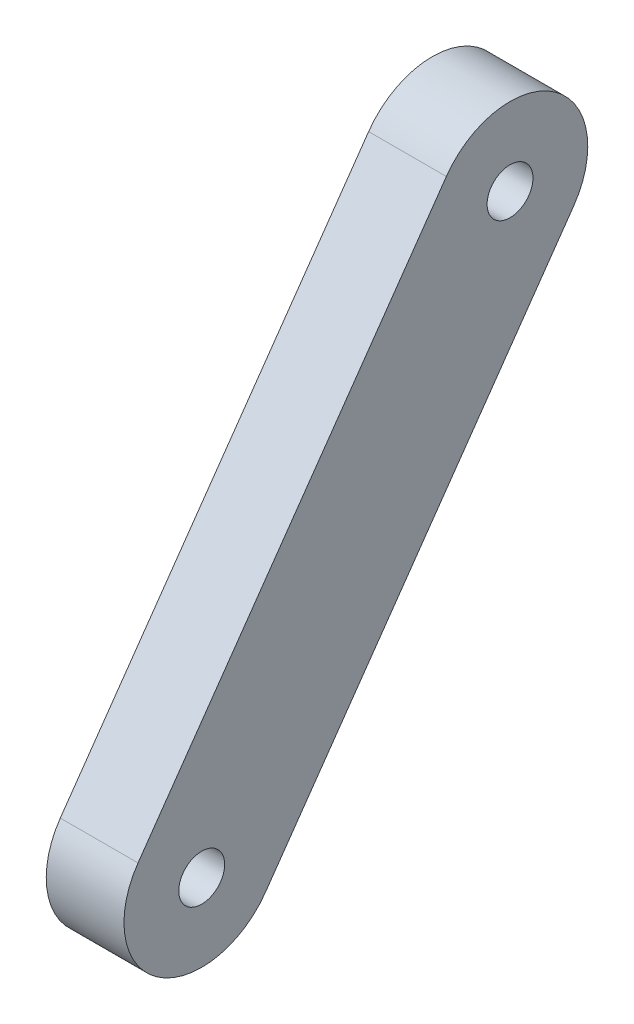
SolidWorks part; units mm, degrees
ref_plane "Front Plane" through (0, 0, 0) normal (0, 0, 1) x (1, 0, 0)
ref_plane "Top Plane" through (0, 0, 0) normal (0, 1, 0) x (1, 0, 0)
ref_plane "Right Plane" through (0, 0, 0) normal (1, 0, 0) x (0, 0, -1)
sketch "Sketch1" plane through (0, 0, 0) normal (1, 0, 0) x (0, 0, -1)
  line L0 (0, 0) -> (16.6734, 0) construction
  line L1 (0, 60.126) -> (20.1478, 88.9) construction
  line L2 (0, 60.126) -> (20.1478, 88.9) construction
  line L3 (-4.1613, 63.0397) -> (15.9865, 91.8138)
  line L4 (4.1613, 57.2122) -> (24.3091, 85.9862)
  arc A0 (-4.1613, 63.0397) -> (4.1613, 57.2122) centre (0, 60.126) ccw
  arc A1 (24.3091, 85.9862) -> (15.9865, 91.8138) centre (20.1478, 88.9) ccw
  circle A2 centre (20.1478, 88.9) radius 1.5
  circle A3 centre (0, 60.126) radius 1.5
  point P6 (10.0739, 74.513)
  dimension "D5" = 3
  dimension "D6" = 3
  dimension "D1" = 60.126
  dimension "D2" = 88.9
  dimension "D3" = 55
  dimension "D4" = 10.16
extrude "Boss-Extrude1" add sketch "Sketch1" along normal mid plane 5.08
